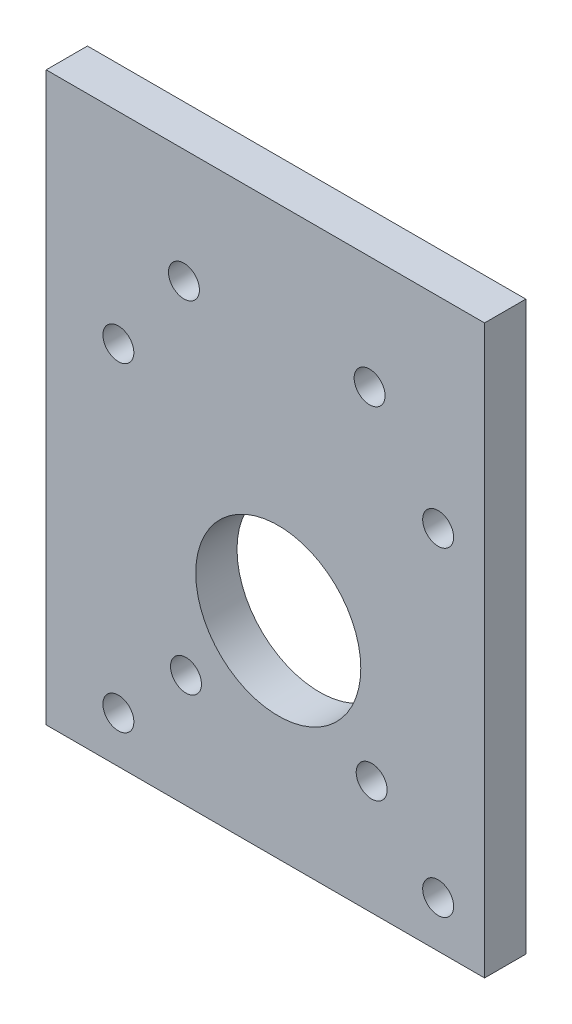
SolidWorks part; units mm, degrees
ref_plane "Front Plane" through (0, 0, 0) normal (0, 0, 1) x (1, 0, 0)
ref_plane "Top Plane" through (0, 0, 0) normal (0, 1, 0) x (1, 0, 0)
ref_plane "Right Plane" through (0, 0, 0) normal (1, 0, 0) x (0, 0, -1)
sketch "Sketch1" plane through (0, 0, 0) normal (0, 0, 1) x (1, 0, 0)
  line L1 (-21.25, 20) -> (21.25, 20)
  line L2 (-21.25, 20) -> (-21.25, -20)
  line L3 (-21.25, -20) -> (21.25, -20)
  line L4 (21.25, 20) -> (21.25, -20)
  line L5 (-21.25, 20) -> (21.25, -20) construction
  line L6 (-21.25, -20) -> (21.25, 20) construction
  point P0 (0, 0)
  dimension "D1" = 42.5
  dimension "D2" = 40
extrude "Boss-Extrude1" add sketch "Sketch1" along normal mid plane 4
sketch "Sketch2" plane through (0, 0, -2) normal (0, 0, -1) x (-1, 0, 0)
  line L0 (21.25, -20) -> (-21.25, -20) construction
  line L1 (-21.25, -20) -> (-21.25, 20) construction
  circle A0 centre (-16.75, 15.5) radius 1.5
  circle A1 centre (14.25, 15.5) radius 1.5
  circle A2 centre (14.25, -15.5) radius 1.5
  circle A3 centre (-16.75, -15.5) radius 1.5
  dimension "D1" = 3
  dimension "D2" = 31
  dimension "D3" = 31
  dimension "D4" = 4.5
  dimension "D5" = 4.5
extrude "Cut-Extrude1" cut sketch "Sketch2" against normal blind 4
sketch "Sketch3" plane through (0, 0, 2) normal (0, 0, 1) x (1, 0, 0)
  line L0 (21.25, -20) -> (21.25, 20) construction
  line L1 (-21.25, -20) -> (21.25, -20) construction
  circle A7 centre (1.25, 0) radius 8
  dimension "D2" = 20
  dimension "D1" = 20
  dimension "D3" = 16
extrude "Cut-Extrude2" cut sketch "Sketch3" against normal blind 4
sketch "Sketch4" plane through (0, 20, 0) normal (0, 1, 0) x (1, 0, 0)
  line L1 (-21.25, 2) -> (21.25, 2)
  line L2 (-21.25, 2) -> (-21.25, -2)
  line L3 (-21.25, -2) -> (21.25, -2)
  line L4 (21.25, 2) -> (21.25, -2)
extrude "Boss-Extrude2" add sketch "Sketch4" along normal blind 15
sketch "Sketch7" plane through (0, 0, 2) normal (0, 0, 1) x (1, 0, 0)
  circle A0 centre (-7.894, 23.9455) radius 1.5
  circle A1 centre (10.1057, 24.0536) radius 1.5
  circle A2 centre (10.3039, -8.9458) radius 1.5
  circle A3 centre (-7.6958, -9.0539) radius 1.5
  dimension "D1" = 3
extrude "Cut-Extrude3" cut sketch "Sketch7" against normal blind 10
